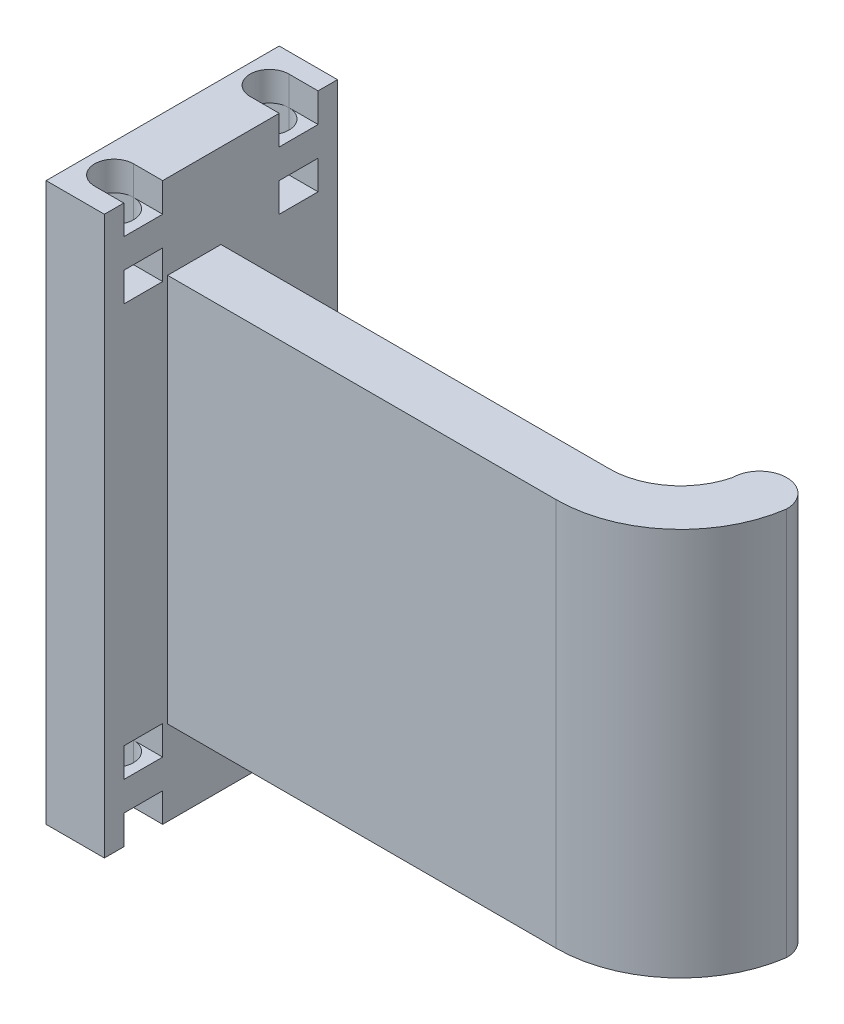
SolidWorks part; units mm, degrees
material "ABS"
ref_plane "Front Plane" through (0, 0, 0) normal (0, 0, 1) x (1, 0, 0)
ref_plane "Top Plane" through (0, 0, 0) normal (0, 1, 0) x (1, 0, 0)
ref_plane "Right Plane" through (0, 0, 0) normal (1, 0, 0) x (0, 0, -1)
sketch "Sketch1" plane through (0, 0, 0) normal (0, 1, 0) x (1, 0, 0)
  line L0 (0, 0) -> (11.2501, 0) construction
  line L15 (15, 6) -> (15, -6)
  line L16 (12, -6) -> (15, -6) construction
  line L17 (15, 6) -> (12, 6)
  line L18 (15, 6) -> (15, -6)
  line L19 (15, -6) -> (12, -6)
  line L20 (12, 6) -> (12, -6)
  line L21 (13.5, -6) -> (13.5, 6) construction
  dimension "D12" = 3
extrude "Boss-Extrude1" add sketch "Sketch1" against normal blind 3
sketch "Esquisse1" plane through (0, 0, 0) normal (0, 1, 0) x (1, 0, 0)
  line L1 (15, 6) -> (12, 6)
  line L2 (15, 6) -> (15, -6)
  line L3 (15, -6) -> (12, -6)
  line L4 (12, 6) -> (12, -6)
extrude "Boss.-Extru.1" add sketch "Esquisse1" along normal blind 25.7
sketch "Esquisse2" plane through (0, 25.7, 0) normal (0, 1, 0) x (1, 0, 0)
  line L0 (13.5, -4) -> (13.5, 4) construction
  line L1 (14.3016, 0) -> (21.3682, 0) construction
  line L2 (12, -6) -> (15, -6) construction
  line L3 (15, 6) -> (12, 6) construction
  line L4 (12, 6) -> (12, -6) construction
  line L5 (15, -6) -> (15, 6) construction
  circle A2 centre (13.5, 4) radius 1
  circle A4 centre (13.5, -4) radius 1
  dimension "D1" = 2
  dimension "D2" = 2
  dimension "D3" = 8
extrude "Enlèv. mat.-Extru.1" cut sketch "Esquisse2" against normal blind 4.5
ref_plane "Plan2" through (21, 0, 0) normal (1, 0, 0) x (0, 0, -1)
sketch "Esquisse10" plane through (0, -3, 0) normal (0, -1, 0) x (1, 0, 0)
  circle A0 centre (13.5, -4) radius 1 construction
  circle A1 centre (13.5, 4) radius 1 construction
  circle A2 centre (13.5, -4) radius 1
  circle A3 centre (13.5, 4) radius 1
extrude "Enlèv. mat.-Extru.3" cut sketch "Esquisse10" against normal blind 4.5
ref_plane "Plan4" through (13.5, 0, 0) normal (-1, 0, 0) x (0, 0, 1)
sketch "Esquisse13" plane through (13.5, 0, 0) normal (-1, 0, 0) x (0, 0, 1)
  line L0 (5.5279, 11.35) -> (-9.8288, 11.35) construction
  line L1 (6, 25.7) -> (-6, 25.7) construction
  line L2 (-6, -3) -> (6, -3) construction
  line L3 (0, 29.2027) -> (0, -5.001) construction
  line L4 (-6, -3) -> (-6, 25.7) construction
  line L5 (6, -3) -> (6, 25.7) construction
  line L7 (5, -1.5) -> (3, -1.5)
  line L8 (5, -1.5) -> (5, -3)
  line L9 (5, -3) -> (3, -3)
  line L10 (3, -1.5) -> (3, -3)
  line L13 (4, -1.5) -> (4, -3) construction
  line L15 (3, -1.5) -> (3, 0) construction
  line L16 (5, 0) -> (3, 0)
  line L17 (5, 0) -> (5, 1.5)
  line L18 (5, 1.5) -> (3, 1.5)
  line L19 (3, 0) -> (3, 1.5)
  line L20 (-3, -1.5) -> (-3, 0) construction
  line L21 (-4, -1.5) -> (-4, -3) construction
  line L22 (-3, 0) -> (-3, 1.5)
  line L23 (-5, 1.5) -> (-3, 1.5)
  line L24 (-5, 0) -> (-5, 1.5)
  line L25 (-5, 0) -> (-3, 0)
  line L26 (-3, -1.5) -> (-3, -3)
  line L27 (-5, -3) -> (-3, -3)
  line L28 (-5, -1.5) -> (-5, -3)
  line L29 (-5, -1.5) -> (-3, -1.5)
  line L30 (-4, 24.2) -> (-4, 25.7) construction
  line L31 (-3, 24.2) -> (-3, 22.7) construction
  line L32 (-5, 24.2) -> (-3, 24.2)
  line L33 (-5, 24.2) -> (-5, 25.7)
  line L34 (-5, 25.7) -> (-3, 25.7)
  line L35 (-3, 24.2) -> (-3, 25.7)
  line L36 (-5, 22.7) -> (-3, 22.7)
  line L37 (-5, 22.7) -> (-5, 21.2)
  line L38 (-5, 21.2) -> (-3, 21.2)
  line L39 (-3, 22.7) -> (-3, 21.2)
  line L40 (3, 24.2) -> (3, 22.7) construction
  line L41 (4, 24.2) -> (4, 25.7) construction
  line L42 (3, 22.7) -> (3, 21.2)
  line L43 (5, 21.2) -> (3, 21.2)
  line L44 (5, 22.7) -> (5, 21.2)
  line L45 (5, 22.7) -> (3, 22.7)
  line L46 (3, 24.2) -> (3, 25.7)
  line L47 (5, 25.7) -> (3, 25.7)
  line L48 (5, 24.2) -> (5, 25.7)
  line L49 (5, 24.2) -> (3, 24.2)
  dimension "D1" = 4
  dimension "D2" = 2
  dimension "D3" = 1.5
extrude "Enlèv. mat.-Extru.5" cut sketch "Esquisse13" against normal blind 5
sketch "Esquisse14" plane through (13.5, 0, 0) normal (-1, 0, 0) x (0, 0, 1)
  line L0 (-4, 0) -> (-4, -1.5) construction
  line L1 (-5, 0) -> (-3, 0)
  line L2 (-5, 0) -> (-5, -1.5)
  line L3 (-5, -1.5) -> (-3, -1.5)
  line L4 (-3, 0) -> (-3, -1.5)
  line L5 (-10.999, 11.35) -> (16.377, 11.35) construction
  line L6 (0, 28.9848) -> (0, -11.8083) construction
  line L7 (-6, 25.7) -> (6, 25.7) construction
  line L8 (-6, -3) -> (6, -3) construction
  line L9 (-6, -3) -> (-6, 25.7) construction
  line L10 (6, -3) -> (6, 25.7) construction
  line L11 (4, 0) -> (4, -1.5) construction
  line L12 (3, 0) -> (3, -1.5)
  line L13 (5, -1.5) -> (3, -1.5)
  line L14 (5, 0) -> (5, -1.5)
  line L15 (5, 0) -> (3, 0)
  line L16 (4, 22.7) -> (4, 24.2) construction
  line L17 (5, 22.7) -> (3, 22.7)
  line L18 (5, 22.7) -> (5, 24.2)
  line L19 (5, 24.2) -> (3, 24.2)
  line L20 (3, 22.7) -> (3, 24.2)
  line L21 (-4, 22.7) -> (-4, 24.2) construction
  line L22 (-3, 22.7) -> (-3, 24.2)
  line L23 (-5, 24.2) -> (-3, 24.2)
  line L24 (-5, 22.7) -> (-5, 24.2)
  line L25 (-5, 22.7) -> (-3, 22.7)
  dimension "D1" = 4
  dimension "D2" = 2
  dimension "D3" = 1.5
  dimension "D4" = 1.5
extrude "Enlèv. mat.-Extru.6" cut sketch "Esquisse14" along normal blind 5
ref_plane "Plane1" through (0, 11.35, 0) normal (0, 1, 0) x (1, 0, 0)
sketch "Sketch2" plane through (0, 11.35, 0) normal (0, 1, 0) x (1, 0, 0)
  line L0 (15, 3) -> (15, -3) construction
  line L1 (15, 0) -> (35, 0)
  line L2 (15, 0) -> (15, -2.7459)
  line L3 (15, -2.7459) -> (35, -2.7459)
  line L4 (35, 0) -> (35, -2.7459)
  line L5 (41.3486, 2.7752) -> (38.5551, 2.7752) construction
  arc A0 (35, -2.7459) -> (41.3486, 2.7752) centre (35, 3.6647) ccw
  arc A1 (35, 0) -> (38.5551, 2.7752) centre (35, 3.6647) ccw
  arc A2 (41.3486, 2.7752) -> (38.5551, 2.7752) centre (39.9518, 2.7752) ccw
  dimension "D1" = 20
extrude "Boss-Extrude2" add sketch "Sketch2" along normal blind 10 and the other way blind 10 contours L4 L1 L2 L3 | A0 L5 A1 L4 | L5 A2
